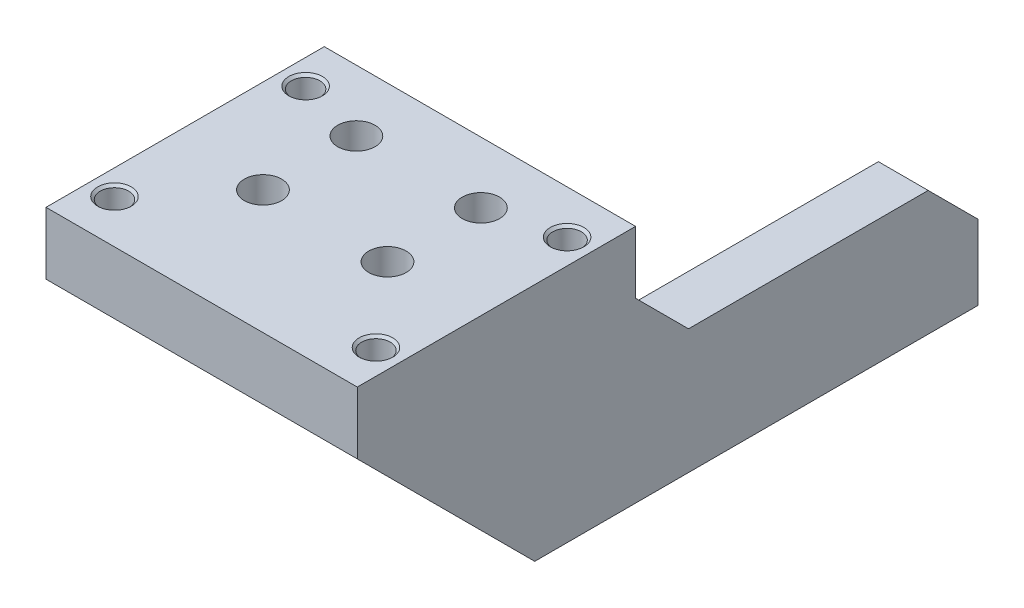
SolidWorks part; units mm, degrees
ref_plane "Front Plane" through (0, 0, 0) normal (0, 0, 1) x (1, 0, 0)
ref_plane "Top Plane" through (0, 0, 0) normal (0, 1, 0) x (1, 0, 0)
ref_plane "Right Plane" through (0, 0, 0) normal (1, 0, 0) x (0, 0, -1)
sketch "Sketch1" plane through (0, 0, 0) normal (0, 1, 0) x (1, 0, 0)
  line L1 (-25, -17.35) -> (25, -17.35)
  line L2 (-25, -17.35) -> (-25, 17.35)
  line L3 (-25, 17.35) -> (25, 17.35)
  line L4 (25, -17.35) -> (25, 17.35)
  line L5 (-25, -17.35) -> (25, 17.35) construction
  line L6 (-25, 17.35) -> (25, -17.35) construction
  point P0 (0, 0)
  dimension "D1" = 50
  dimension "D2" = 34.7
extrude "Boss-Extrude1" add sketch "Sketch1" along normal blind 10
sketch "Sketch2" plane through (0, 10, 0) normal (0, 1, 0) x (1, 0, 0)
  line L1 (-10, -7.5) -> (10, -7.5) construction
  line L2 (-10, -7.5) -> (-10, 7.5) construction
  line L3 (-10, 7.5) -> (10, 7.5) construction
  line L4 (10, -7.5) -> (10, 7.5) construction
  line L5 (-10, -7.5) -> (10, 7.5) construction
  line L6 (-10, 7.5) -> (10, -7.5) construction
  circle A0 centre (-10, 7.5) radius 1.75
  circle A1 centre (10, 7.5) radius 1.75
  circle A2 centre (10, -7.5) radius 1.75
  circle A3 centre (-10, -7.5) radius 1.75
  point P0 (0, 0)
  dimension "D1" = 3.5
  dimension "D2" = 20
  dimension "D3" = 15
extrude "Cut-Extrude1" cut sketch "Sketch2" against normal up to next
sketch "Sketch3" plane through (0, 10, 0) normal (0, 1, 0) x (1, 0, 0)
  circle A3 centre (-10, 7.5) radius 3
  circle A4 centre (10, 7.5) radius 3
  circle A5 centre (10, -7.5) radius 3
  circle A6 centre (-10, -7.5) radius 3
  dimension "D1" = 6
extrude "Cut-Extrude2" cut sketch "Sketch3" against normal blind 5
sketch "Sketch6" plane through (0, 0, 0) normal (0, -1, 0) x (1, 0, 0)
  line L0 (25, 17.35) -> (25, -17.35) construction
  line L1 (-25, 17.35) -> (25, 17.35)
  line L2 (-25, 17.35) -> (-25, 27.35)
  line L3 (-25, 27.35) -> (25, 27.35)
  line L4 (25, 17.35) -> (25, 27.35)
  dimension "D1" = 10
extrude "Boss-Extrude3" add sketch "Sketch6" against normal up to surface (10 mm away) up to face at (-10, 10, -4.5)
sketch "Sketch8" plane through (25, 0, 0) normal (1, 0, 0) x (0, 0, -1)
  line L0 (-27.35, 0) -> (17.35, 0)
  line L1 (-27.35, 0) -> (17.35, 0) construction
  line L2 (17.35, 0) -> (25.85, -8.5)
  line L3 (25.85, -8.5) -> (72.35, -8.5)
  line L4 (72.35, -8.5) -> (72.35, -28.5)
  line L5 (72.35, -28.5) -> (1.15, -28.5)
  line L6 (1.15, -28.5) -> (-27.35, 0)
  line L7 (17.35, 10) -> (17.35, 0) construction
  dimension "D1" = 28.5
  dimension "D2" = 20
  dimension "D3" = 45
  dimension "D4" = 55
extrude "Boss-Extrude4" add sketch "Sketch8" against normal blind 8
chamfer "Chamfer1" distance 8 angle 45 1 edges at (21, -8.5, -72.35)
sketch "Sketch10" plane through (0, 10, 0) normal (0, 1, 0) x (1, 0, 0)
  line L0 (25, 17.35) -> (-25, 17.35) construction
  line L1 (25, -27.35) -> (25, 17.35) construction
  circle A0 centre (21, 10.35) radius 2.3
  dimension "D1" = 4.6
  dimension "D2" = 4
  dimension "D3" = 7
extrude "Cut-Extrude3" cut sketch "Sketch10" against normal blind 4.8
ref_plane "Plane1" through (0, 0, 5) normal (0, 0, -1) x (-1, 0, 0)
mirror "Mirror1" about plane through (0, 0, 5) normal (0, 0, -1) of "Cut-Extrude3"
ref_plane "Plane2" through (0, 0, 0) normal (-1, 0, 0) x (0, 0, 1)
mirror "Mirror2" about plane through (0, 0, 0) normal (-1, 0, 0) of "Mirror1", "Cut-Extrude3"
chamfer "Chamfer2" distance 0.4 angle 45 4 edges at (21, 10, -8.05) (-21, 10, -8.05) (-21, 10, 18.05) (21, 10, 18.05)
